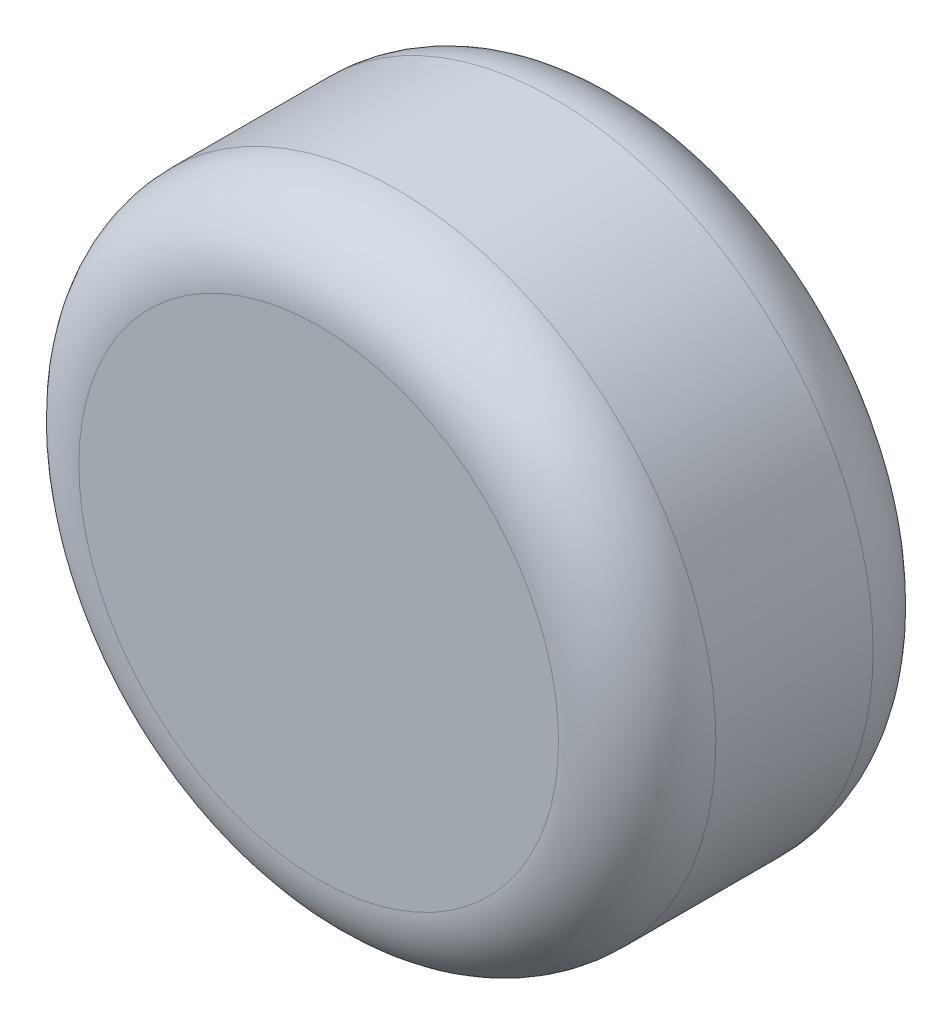
SolidWorks part; units mm, degrees
ref_plane "前视基准面" through (0, 0, 0) normal (0, 0, 1) x (1, 0, 0)
ref_plane "上视基准面" through (0, 0, 0) normal (0, 1, 0) x (1, 0, 0)
ref_plane "右视基准面" through (0, 0, 0) normal (1, 0, 0) x (0, 0, -1)
sketch "草图1" plane through (0, 0, 0) normal (0, 0, 1) x (1, 0, 0)
  circle A0 centre (0, 0) radius 20.25
  dimension "D1" = 40.5
extrude "凸台-拉伸1" add sketch "草图1" along normal blind 20
fillet "圆角1" radius 5 2 edges at (20.25, 0, 0) (20.25, 0, 20)
ref_plane "基准面1" through (-20.25, 0, 0) normal (-1, 0, 0) x (0, 0, 1)
sketch "草图2" plane through (-20.25, 0, 0) normal (-1, 0, 0) x (0, 0, 1)
  line L0 (5, 0) -> (15, 0) construction
  line L1 (5, 20.25) -> (5, -20.25) construction
  line L2 (15, -20.25) -> (15, 20.25) construction
sketch "草图3" plane through (0, 0, 0) normal (0, 0, -1) x (-1, 0, 0)
  line L0 (0, 0) -> (21.6986, 0) construction
